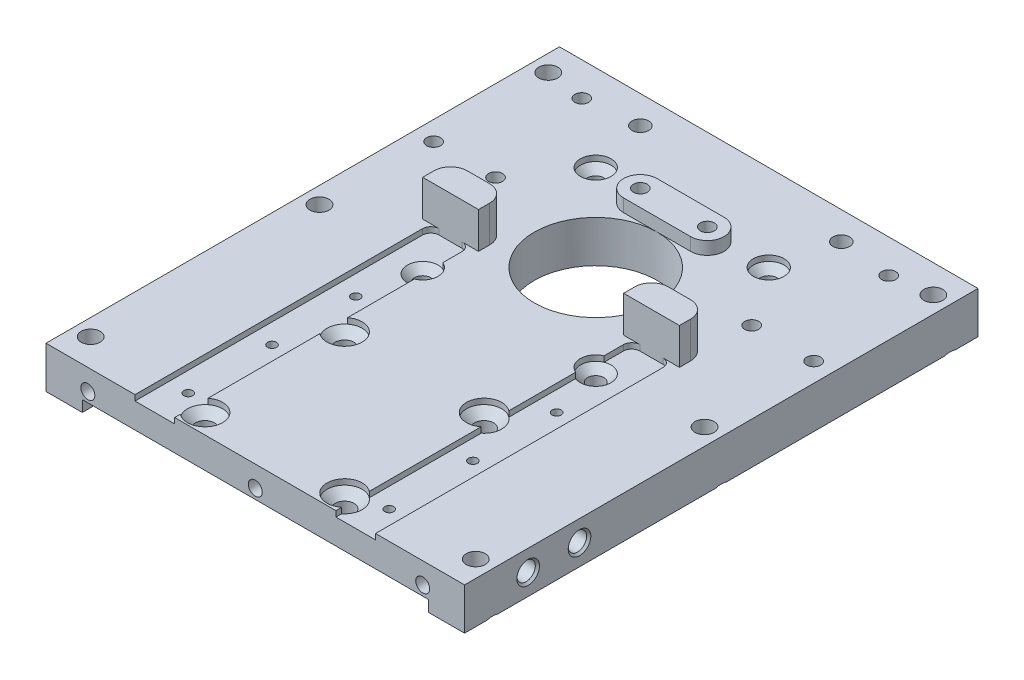
SolidWorks part; units mm, degrees
material "3.1355 (EN-AW 2024)"
ref_plane "Спереди" through (0, 0, 0) normal (0, 0, 1) x (1, 0, 0)
ref_plane "Сверху" through (0, 0, 0) normal (0, 1, 0) x (1, 0, 0)
ref_plane "Справа" through (0, 0, 0) normal (1, 0, 0) x (0, 0, -1)
sketch "Эскиз1" plane through (0, 0, 0) normal (0, 1, 0) x (1, 0, 0)
  line L1 (-37.5, 71) -> (37.5, 71)
  line L2 (-37.5, 71) -> (-37.5, -21)
  line L3 (-37.5, -21) -> (37.5, -21)
  line L4 (37.5, 71) -> (37.5, -21)
  point P7 (0, -21)
  dimension "D1" = 75
  dimension "D2" = 71
  dimension "D3" = 21
extrude "База" add sketch "Эскиз1" along normal blind 7.5
sketch "Эскиз16" plane through (0, 7.5, 0) normal (0, 1, 0) x (1, 0, 0)
  line L5 (-37.5, -21) -> (37.5, -21) construction
  line L7 (-14.45, 5.5) -> (0, 5.5) construction
  line L8 (0, 5.5) -> (14.45, 5.5) construction
  line L10 (-21.55, 32) -> (-21.55, -21)
  line L11 (-21.55, -21) -> (-14.45, -21)
  line L12 (-14.45, 32) -> (-14.45, -21)
  line L19 (21.55, -21) -> (14.45, -21)
  line L20 (21.55, -21) -> (21.55, 32)
  line L22 (14.45, -21) -> (14.45, 32)
  line L23 (-21.55, 32) -> (-14.45, 32)
  line L25 (14.45, 32) -> (21.55, 32)
  point P17 (-18, -21)
  point P18 (18, -21)
  dimension "D2" = 36
  dimension "D3" = 53
  dimension "D5" = 7.1
extrude "Рельсы" cut sketch "Эскиз16" against normal blind 1
hole_wizard "Рельсы M3" positions "Эскиз59" profile "Эскиз60" tap size "M2" standard "ISO" end condition through all
sketch "Эскиз59" plane through (0, 6.5, 0) normal (0, 1, 0) x (1, 0, 0)
  line L0 (-21.55, -21) -> (-14.45, -21) construction
  line L1 (14.45, -21) -> (21.55, -21) construction
  line L27 (-18, -15) -> (-18, -21) construction
  point P0 (-18, -15)
  point P2 (18, -15)
  point P7 (-18, -21)
  point P10 (18, -21)
  dimension "D1" = 6
sketch "Эскиз60" plane through (-18, 6.5, 15) normal (1, 0, 0) x (0, 0, 1)
  line L0 (0, 0) -> (0, 6.5)
  line L1 (0, 6.5) -> (0.8, 6.5)
  line L2 (0.8, 6.5) -> (0.8, 0)
  line L5 (0.8, 0) -> (0, 0)
  line L11 (0, -6.35) -> (0, 107.95) construction
  dimension "Диаметр проходного сверла" = 1.6
  dimension "Глубина проходного сверла" = 6.5
cosmetic thread "Отверстие резьбы13" parameters "D2"=2
cosmetic thread "Отверстие резьбы14" parameters "D2"=2
hole_wizard "Каретка 15 - M3" positions "Эскиз55" profile "Эскиз56" countersink size "M3" standard "DIN" end condition up to next
sketch "Эскиз55" plane through (0, 7.5, 0) normal (0, 1, 0) x (1, 0, 0)
  line L15 (-12.5, -17.5) -> (12.5, -17.5) construction
  line L16 (12.5, -17.5) -> (12.5, 7.5) construction
  point P45 (-12.5, -17.5)
  point P46 (12.5, -17.5)
  point P47 (12.5, 7.5)
  point P48 (-12.5, 7.5)
  point P53 (0, -17.5)
  point P59 (12.5, -5)
  dimension "D1" = 25
  dimension "D2" = 5
  dimension "D5" = 25
sketch "Эскиз56" plane through (-12.5, 7.5, -7.5) normal (1, 0, 0) x (0, 0, 1)
  line L0 (0, 0) -> (0, 7.5)
  line L1 (0, 7.5) -> (1.7, 7.5)
  line L2 (1.7, 7.5) -> (1.7, 2.45)
  line L3 (1.7, 2.45) -> (3.15, 1)
  line L4 (3.15, 1) -> (3.15, 0)
  line L6 (3.15, 0) -> (0, 0)
  line L7 (-1.7, 2.45) -> (-3.15, 1) construction
  line L11 (0, -6.35) -> (0, 107.95) construction
  dimension "Диаметр сквозного отверстия" = 3.4
  dimension "Глубина сквозного отверстия" = 7.5
  dimension "Диаметр зенковки" = 6.3
  dimension "Угол зенковки" = 90
  dimension "Утопленность" = 1
sketch "Эскиз28" plane through (0, 7.5, 0) normal (0, 1, 0) x (1, 0, 0)
  circle A3 centre (0, 40) radius 11
  dimension "D1" = 22
  dimension "D2" = 40
extrude "Двигатель" cut sketch "Эскиз28" against normal through all
hole_wizard "Крепление двигателя" positions "Эскиз29" profile "Эскиз31" countersink size "M2.5" standard "DIN" end condition through all
sketch "Эскиз29" plane through (0, 7.5, 0) normal (0, 1, 0) x (1, 0, 0)
  line L0 (-15.5, 55.5) -> (0, 55.5) construction
  line L1 (0, 55.5) -> (15.5, 55.5) construction
  line L2 (15.5, 55.5) -> (15.5, 40) construction
  line L3 (15.5, 40) -> (15.5, 24.5) construction
  circle A0 centre (0, 40) radius 11 construction
  point P0 (-15.5, 55.5)
  point P2 (15.5, 55.5)
  point P4 (15.5, 24.5)
  point P6 (-15.5, 24.5)
  dimension "D1" = 31
  dimension "D2" = 0
sketch "Эскиз31" plane through (-15.5, 7.5, -55.5) normal (1, 0, 0) x (0, 0, 1)
  line L0 (0, 0) -> (0, 7.5)
  line L1 (0, 7.5) -> (1.45, 7.5)
  line L2 (1.45, 7.5) -> (1.45, 2.3)
  line L3 (1.45, 2.3) -> (2.75, 1)
  line L4 (2.75, 1) -> (2.75, 0)
  line L6 (2.75, 0) -> (0, 0)
  line L7 (-1.45, 2.3) -> (-2.75, 1) construction
  line L11 (0, -6.35) -> (0, 107.95) construction
  dimension "Диаметр сквозного отверстия" = 2.9
  dimension "Глубина сквозного отверстия" = 7.5
  dimension "Диаметр зенковки" = 5.5
  dimension "Угол зенковки" = 90
  dimension "Утопленность" = 1
sketch "Эскиз90" plane through (0, 7.5, 0) normal (0, 1, 0) x (1, 0, 0)
  line L0 (21.55, 32) -> (14.45, 32) construction
  line L1 (23, 32) -> (13, 32)
  line L2 (23, 32) -> (23, 37)
  line L3 (23, 37) -> (13, 37)
  line L4 (13, 32) -> (13, 37)
  line L5 (-14.45, 32) -> (-21.55, 32) construction
  line L6 (-23, 37) -> (-13, 37)
  line L7 (-23, 37) -> (-23, 32)
  line L8 (-23, 32) -> (-13, 32)
  line L9 (-13, 37) -> (-13, 32)
  point P7 (18, 32)
  point P8 (18, 32)
  point P15 (-18, 32)
  point P16 (-18, 32)
  dimension "D1" = 10
  dimension "D2" = 5
extrude "Стопор" add sketch "Эскиз90" along normal blind 6.5
sketch "Эскиз87" plane through (0, 7.5, 0) normal (0, 1, 0) x (1, 0, 0)
  line L0 (-6, 54) -> (6, 54) construction
  line L1 (-6, 57) -> (6, 57)
  line L2 (-6, 51) -> (6, 51)
  arc A0 (-6, 57) -> (-6, 51) centre (-6, 54) ccw
  arc A1 (6, 51) -> (6, 57) centre (6, 54) ccw
  circle A2 centre (0, 40) radius 11 construction
  point P4 (0, 54)
  dimension "D2" = 3
  dimension "D1" = 12
extrude "ДатчикВынос" add sketch "Эскиз87" along normal blind 2.3
hole_wizard "Датчик M3" positions "Эскиз42" profile "Эскиз43" tap size "M3" standard "DIN" end condition through all
sketch "Эскиз42" plane through (0, 9.8, 0) normal (0, -1, 0) x (-1, 0, 0)
  line L1 (6, 54) -> (0, 54) construction
  line L2 (0, 54) -> (-6, 54) construction
  circle A0 centre (0, 40) radius 11 construction
  point P0 (6, 54)
  point P4 (-6, 54)
  dimension "D1" = 14
  dimension "D3" = 12
sketch "Эскиз43" plane through (-6, 9.8, -54) normal (1, 0, 0) x (0, 0, 1)
  line L0 (0, 0) -> (0, 9.8)
  line L1 (0, 9.8) -> (1.25, 9.8)
  line L2 (1.25, 9.8) -> (1.25, 0)
  line L5 (1.25, 0) -> (0, 0)
  line L11 (0, -6.35) -> (0, 107.95) construction
  dimension "Диаметр проходного сверла" = 2.5
  dimension "Глубина проходного сверла" = 9.8
cosmetic thread "Отверстие резьбы71" parameters "D1"=6, "D2"=3
cosmetic thread "Отверстие резьбы72" parameters "D1"=6, "D2"=3
sketch "Эскиз77" plane through (0, 0, 0) normal (0, -1, 0) x (1, 0, 0)
  line L0 (-12.5, 17.5) -> (12.5, -7.5) construction
  line L1 (12.5, 17.5) -> (0, 5) construction
  line L2 (0, 5) -> (-12.5, -7.5) construction
  line L4 (-31, 22) -> (31, 22)
  line L5 (-31, 22) -> (-31, -12)
  line L6 (-31, -12) -> (31, -12)
  line L7 (31, 22) -> (31, -12)
  line L8 (-31, 22) -> (31, -12) construction
  line L9 (-31, -12) -> (31, 22) construction
  dimension "D1" = 62
  dimension "D2" = 34
extrude "Вырез-Вытянуть1" cut sketch "Эскиз77" against normal blind 2
hole_wizard "Верх-M3" positions "Эскиз51" profile "Эскиз53" tap size "M3" standard "DIN"
sketch "Эскиз51" plane through (0, 0, -71) normal (0, 0, -1) x (-1, 0, 0)
  line L0 (0, 0) -> (0, 3.75) construction
  line L1 (0, 3.75) -> (0, 7.5) construction
  line L2 (-37.5, 7.5) -> (37.5, 7.5) construction
  line L5 (-30, 3.75) -> (0, 3.75) construction
  line L6 (0, 3.75) -> (30, 3.75) construction
  point P0 (-30, 3.75)
  point P3 (0, 3.75)
  point P6 (30, 3.75)
  dimension "D1" = 60
sketch "Эскиз53" plane through (30, 3.75, -71) normal (1, 0, 0) x (0, 1, 0)
  line L0 (0, 0) -> (0, 5.7511)
  line L1 (0, 5.7511) -> (1.25, 5)
  line L2 (1.25, 5) -> (1.25, 0.275)
  line L3 (1.25, 0.275) -> (1.525, 0)
  line L5 (1.525, 0) -> (0, 0)
  line L6 (-1.25, 0.275) -> (-1.525, 0) construction
  line L10 (0, 5.7511) -> (-1.25, 5) construction
  line L11 (0, -6.35) -> (0, 107.95) construction
  dimension "Диаметр сверла" = 2.5
  dimension "Глубина сверла" = 5
  dimension "Диаметр передней зенковки" = 3.05
  dimension "Угол передней зенковки" = 90
  dimension "Угол заточки сверла" = 118
cosmetic thread "Отверстие резьбы42" parameters "D1"=5, "D2"=3
cosmetic thread "Отверстие резьбы43" parameters "D1"=5, "D2"=3
cosmetic thread "Отверстие резьбы44" parameters "D1"=5, "D2"=3
hole_wizard "Низ-M3" positions "Эскиз46" profile "Эскиз47" tap size "M3" standard "ISO"
sketch "Эскиз46" plane through (0, 0, 21) normal (0, 0, 1) x (1, 0, 0)
  line L0 (0, 0) -> (0, 3.75) construction
  line L1 (0, 3.75) -> (0, 7.5) construction
  line L2 (37.5, 7.5) -> (-37.5, 7.5) construction
  line L11 (-30, 3.75) -> (0, 3.75) construction
  line L12 (0, 3.75) -> (30, 3.75) construction
  point P0 (-30, 3.75)
  point P3 (0, 3.75)
  point P6 (30, 3.75)
  dimension "D1" = 60
sketch "Эскиз47" plane through (-30, 3.75, 21) normal (1, 0, 0) x (0, -1, 0)
  line L0 (0, 0) -> (0, 5.7511)
  line L1 (0, 5.7511) -> (1.25, 5)
  line L2 (1.25, 5) -> (1.25, 0)
  line L5 (1.25, 0) -> (0, 0)
  line L10 (0, 5.7511) -> (-1.25, 5) construction
  line L11 (0, -6.35) -> (0, 107.95) construction
  dimension "Диаметр сверла" = 2.5
  dimension "Глубина сверла" = 5
  dimension "Угол заточки сверла" = 118
cosmetic thread "Отверстие резьбы39" parameters "D1"=5, "D2"=3
cosmetic thread "Отверстие резьбы40" parameters "D1"=5, "D2"=3
cosmetic thread "Отверстие резьбы41" parameters "D1"=5, "D2"=3
hole_wizard "Стенки-M3" positions "Эскиз64" profile "Эскиз65" countersink size "M3" standard "ISO" end condition through all
sketch "Эскиз64" plane through (0, 0, 0) normal (0, -1, 0) x (-1, 0, 0)
  line L0 (34.5, -16) -> (34.5, 25) construction
  line L1 (34.5, 25) -> (34.5, 66) construction
  line L4 (-34.5, 66) -> (-34.5, 25) construction
  line L5 (-34.5, 25) -> (-34.5, -16) construction
  line L8 (37.5, 71) -> (37.5, -21) construction
  line L9 (-37.5, -21) -> (-37.5, 71) construction
  point P0 (34.5, 25)
  point P2 (34.5, -16)
  point P4 (34.5, 66)
  point P6 (-34.5, 66)
  point P8 (-34.5, 25)
  point P10 (-34.5, -16)
  point P26 (37.5, 25)
  dimension "D1" = 3
  dimension "D2" = 3
  dimension "D3" = 82
sketch "Эскиз65" plane through (-34.5, 0, -25) normal (1, 0, 0) x (0, 0, -1)
  line L0 (0, 0) -> (0, 14)
  line L1 (0, 14) -> (1.7, 14)
  line L2 (1.7, 14) -> (1.7, 1.45)
  line L3 (1.7, 1.45) -> (3.15, 0)
  line L5 (3.15, 0) -> (0, 0)
  line L6 (-1.7, 1.45) -> (-3.15, 0) construction
  line L11 (0, -6.35) -> (0, 107.95) construction
  dimension "Диаметр сквозного отверстия" = 3.4
  dimension "Глубина сквозного отверстия" = 14
  dimension "Диаметр передней зенковки" = 6.3
  dimension "Угол передней зенковки" = 90
sketch "Эскиз63" plane through (0, 7.5, 0) normal (0, 1, 0) x (1, 0, 0)
  line L0 (37.5, 71) -> (-37.5, 71) construction
  line L4 (-18, 66) -> (0, 66) construction
  line L5 (0, 66) -> (18, 66) construction
  circle A0 centre (-18, 66) radius 1.495
  circle A1 centre (18, 66) radius 1.495
  dimension "D1" = 2.99
  dimension "D2" = 5
  dimension "D3" = 36
extrude "Клапана" cut sketch "Эскиз63" against normal through all
fillet "Скругление2" radius 1.5 6 edges at (-31, 1, -12) (31, 1, -12) (14.45, 7, -32) (21.55, 7, -32) (-14.45, 7, -32) (-21.55, 7, -32)
pattern_linear "Линейный массив2" count 3 spacing 15 along (0, 0, -1) of "Рельсы M3"
hole_wizard "Трос1-M4" positions "Эскиз81" profile "Эскиз82" tap size "M4" standard "DIN"
sketch "Эскиз81" plane through (-37.5, 0, 0) normal (-1, 0, 0) x (0, 0, 1)
  line L0 (0.4, 3.75) -> (0.4, 7.5) construction
  line L1 (-71, 7.5) -> (21, 7.5) construction
  line L4 (0.4, 3.75) -> (0.4, 0) construction
  line L5 (-24.0395, 0) -> (15.0395, 0) construction
  point P0 (0.4, 3.75)
  point P37 (9.6, 3.75)
  dimension "D1" = 0.4
  dimension "D2" = 9.2
sketch "Эскиз82" plane through (-37.5, 3.75, 0.4) normal (0, 1, 0) x (0, 0, 1)
  line L0 (0, 0) -> (0, 16.9914)
  line L1 (0, 16.9914) -> (1.65, 16)
  line L2 (1.65, 16) -> (1.65, 0.375)
  line L3 (1.65, 0.375) -> (2.025, 0)
  line L5 (2.025, 0) -> (0, 0)
  line L6 (-1.65, 0.375) -> (-2.025, 0) construction
  line L10 (0, 16.9914) -> (-1.65, 16) construction
  line L11 (0, -6.35) -> (0, 107.95) construction
  dimension "Диаметр сверла" = 3.3
  dimension "Глубина сверла" = 16
  dimension "Диаметр передней зенковки" = 4.05
  dimension "Угол передней зенковки" = 90
  dimension "Угол заточки сверла" = 118
cosmetic thread "Отверстие резьбы60" parameters "D1"=14, "D2"=4
cosmetic thread "Отверстие резьбы75" parameters "D1"=14, "D2"=4
hole_wizard "Трос2-М3" positions "Эскиз83" profile "Эскиз84" tap size "M4" standard "DIN"
sketch "Эскиз83" plane through (37.5, 0, 0) normal (1, 0, 0) x (0, 0, -1)
  point P9 (-0.4, 3.75)
  point P14 (-9.6, 3.75)
sketch "Эскиз84" plane through (37.5, 3.75, 0.4) normal (0, 1, 0) x (0, 0, -1)
  line L0 (0, 0) -> (0, 16.9914)
  line L1 (0, 16.9914) -> (1.65, 16)
  line L2 (1.65, 16) -> (1.65, 0.375)
  line L3 (1.65, 0.375) -> (2.025, 0)
  line L5 (2.025, 0) -> (0, 0)
  line L6 (-1.65, 0.375) -> (-2.025, 0) construction
  line L10 (0, 16.9914) -> (-1.65, 16) construction
  line L11 (0, -6.35) -> (0, 107.95) construction
  dimension "Диаметр сверла" = 3.3
  dimension "Глубина сверла" = 16
  dimension "Диаметр передней зенковки" = 4.05
  dimension "Угол передней зенковки" = 90
  dimension "Угол заточки сверла" = 118
cosmetic thread "Отверстие резьбы61" parameters "D1"=14, "D2"=4
cosmetic thread "Отверстие резьбы76" parameters "D1"=14, "D2"=4
hole_wizard "Концевики-M3" positions "Эскиз85" profile "Эскиз86" tap size "M3" standard "DIN" end condition through all
sketch "Эскиз85" plane through (0, 0, 0) normal (0, -1, 0) x (-1, 0, 0)
  line L0 (34.05, 45) -> (22.95, 45) construction
  line L3 (-22.95, 45) -> (-34.05, 45) construction
  line L10 (22.95, 45) -> (0, 45) construction
  line L11 (0, 45) -> (-22.95, 45) construction
  point P0 (34.05, 45)
  point P3 (22.95, 45)
  point P6 (-34.05, 45)
  point P9 (-22.95, 45)
  point P40 (28.5, 45)
  point P41 (-28.5, 45)
  dimension "D1" = 11.1
  dimension "D2" = 57
  dimension "D3" = 45
sketch "Эскиз86" plane through (-34.05, 0, -45) normal (1, 0, 0) x (0, 0, -1)
  line L0 (0, 0) -> (0, 14)
  line L1 (0, 14) -> (1.25, 14)
  line L2 (1.25, 14) -> (1.25, 0)
  line L5 (1.25, 0) -> (0, 0)
  line L11 (0, -6.35) -> (0, 107.95) construction
  dimension "Диаметр проходного сверла" = 2.5
  dimension "Глубина проходного сверла" = 14
cosmetic thread "Отверстие резьбы63" parameters "D2"=3
cosmetic thread "Отверстие резьбы64" parameters "D2"=3
cosmetic thread "Отверстие резьбы65" parameters "D2"=3
cosmetic thread "Отверстие резьбы66" parameters "D2"=3
hole_wizard "Пружина-М3" positions "Эскиз88" profile "Эскиз89" tap size "M3" standard "DIN" end condition through all
sketch "Эскиз88" plane through (0, 7.5, 0) normal (0, 1, 0) x (1, 0, 0)
  line L0 (27.5, 65) -> (0, 65) construction
  line L1 (0, 65) -> (-27.5, 65) construction
  point P0 (-27.5, 65)
  point P2 (27.5, 65)
  dimension "D1" = 55
  dimension "D2" = 65
sketch "Эскиз89" plane through (-27.5, 7.5, -65) normal (1, 0, 0) x (0, 0, 1)
  line L0 (0, 0) -> (0, 7.5)
  line L1 (0, 7.5) -> (1.25, 7.5)
  line L2 (1.25, 7.5) -> (1.25, 0)
  line L5 (1.25, 0) -> (0, 0)
  line L11 (0, -6.35) -> (0, 107.95) construction
  dimension "Диаметр проходного сверла" = 2.5
  dimension "Глубина проходного сверла" = 7.5
cosmetic thread "Отверстие резьбы73" parameters "D1"=7.5, "D2"=3
cosmetic thread "Отверстие резьбы74" parameters "D1"=7.5, "D2"=3
fillet "Скругление3" radius 3 4 edges at (-13, 10.75, -37) (-23, 10.75, -37) (13, 10.75, -37) (23, 10.75, -37)
